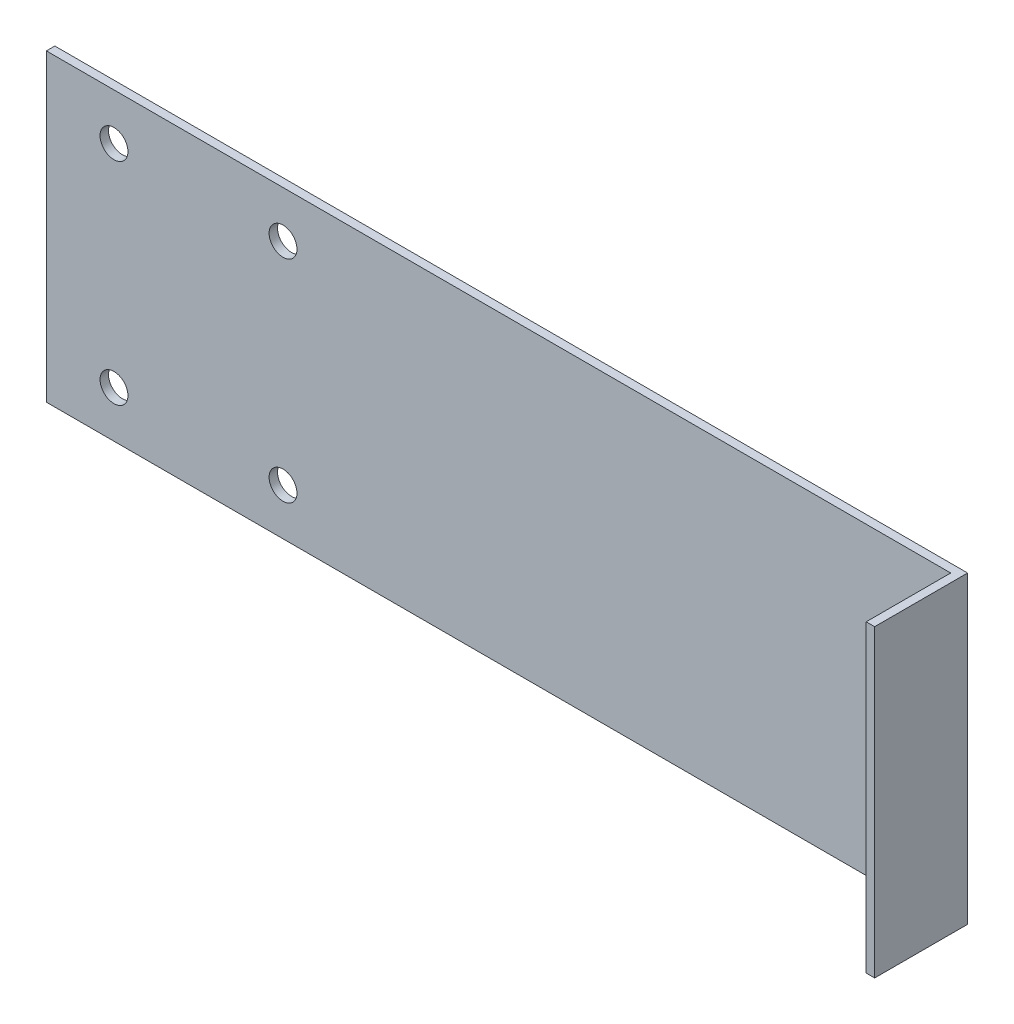
SolidWorks part; units mm, degrees
ref_plane "前视基准面" through (0, 0, 0) normal (0, 0, 1) x (1, 0, 0)
ref_plane "上视基准面" through (0, 0, 0) normal (0, 1, 0) x (1, 0, 0)
ref_plane "右视基准面" through (0, 0, 0) normal (1, 0, 0) x (0, 0, -1)
sketch "草图1" plane through (0, 0, 0) normal (0, 0, 1) x (1, 0, 0)
  line L1 (-54, 18) -> (54, 18)
  line L2 (-54, 18) -> (-54, -18)
  line L3 (-54, -18) -> (54, -18)
  line L4 (54, 18) -> (54, -18)
  line L5 (-54, 18) -> (54, -18) construction
  line L6 (-54, -18) -> (54, 18) construction
  point P0 (0, 0)
  dimension "D1" = 36
  dimension "D2" = 108
extrude "凸台-拉伸1" add sketch "草图1" along normal blind 1
sketch "草图2" plane through (0, 0, 1) normal (0, 0, 1) x (1, 0, 0)
  line L0 (-1000, 0) -> (49000, 0) construction
  line L1 (-54, 18) -> (-54, -18) construction
  circle A0 centre (-46, -12.5) radius 2
  circle A1 centre (-26, -12.5) radius 2
  dimension "D1" = 8
  dimension "D2" = 12.5
  dimension "D3" = 20
hole_wizard "M4 螺纹孔的螺纹孔钻头1" positions "3D草图1" profile "草图3" hole size "M4" standard "GB"
sketch3d "3D草图1"
  point P0 (-46, -12.5, 1)
  point P3 (-26, -12.5, 1)
sketch "草图3" plane through (-46, -12.5, 1) normal (1, 0, 0) x (0, -1, 0)
  line L0 (0, 0) -> (0, 10.9914)
  line L1 (0, 10.9914) -> (1.65, 10)
  line L2 (1.65, 10) -> (1.65, 0)
  line L5 (1.65, 0) -> (0, 0)
  line L10 (0, 10.9914) -> (-1.65, 10) construction
  line L11 (0, -6.35) -> (0, 107.95) construction
  dimension "孔直径" = 3.3
  dimension "孔深度" = 10
  dimension "导头角度" = 118
mirror "镜向1" about plane through (0, 0, 0) normal (0, 1, 0) of "M4 螺纹孔的螺纹孔钻头1"
sketch "草图4" plane through (0, 0, 1) normal (0, 0, 1) x (1, 0, 0)
  line L0 (54, 18) -> (-54, 18) construction
  line L4 (53, 18) -> (54, 18)
  line L5 (53, 18) -> (53, -18)
  line L6 (53, -18) -> (54, -18)
  line L7 (54, 18) -> (54, -18)
  dimension "D1" = 1
extrude "凸台-拉伸2" add sketch "草图4" along normal blind 10
